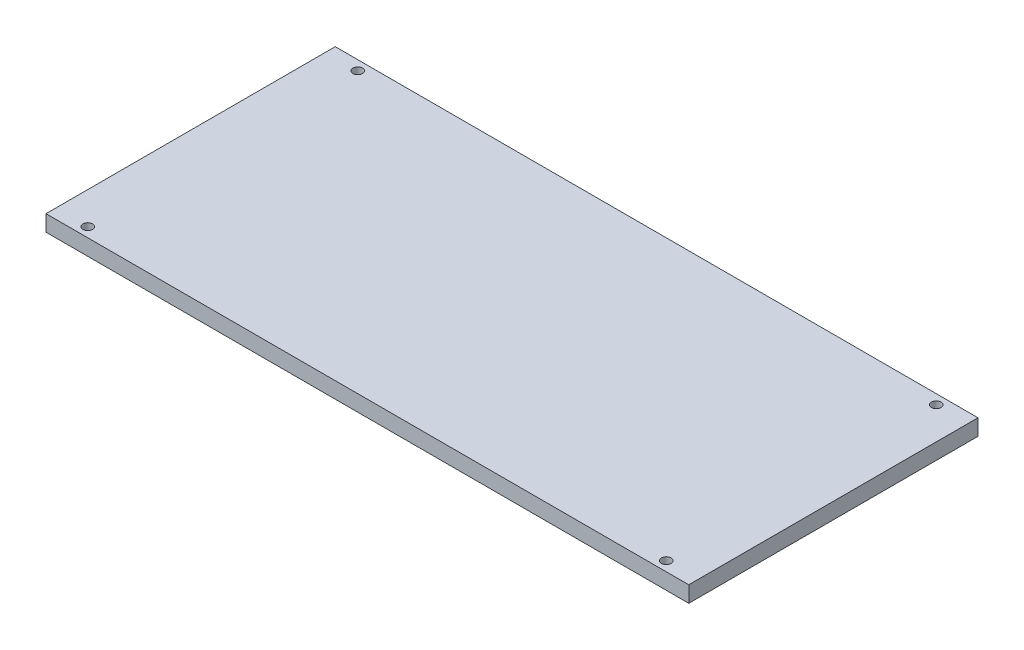
SolidWorks part; units mm, degrees
ref_plane "Front Plane" through (0, 0, 0) normal (0, 0, 1) x (1, 0, 0)
ref_plane "Top Plane" through (0, 0, 0) normal (0, 1, 0) x (1, 0, 0)
ref_plane "Right Plane" through (0, 0, 0) normal (1, 0, 0) x (0, 0, -1)
sketch "Sketch1" plane through (0, 0, 0) normal (0, 1, 0) x (1, 0, 0)
  line L1 (-96.0207, -6.3578) -> (103.9793, -6.3578)
  line L2 (-96.0207, -6.3578) -> (-96.0207, -96.3578)
  line L3 (-96.0207, -96.3578) -> (103.9793, -96.3578)
  line L4 (103.9793, -6.3578) -> (103.9793, -96.3578)
  circle A0 centre (-86.0207, -9.3578) radius 1.5
  circle A1 centre (-86.0207, -93.3578) radius 1.5
  circle A2 centre (93.9793, -9.3578) radius 1.5
  circle A3 centre (93.9793, -93.3578) radius 1.5
  point P12 (0, 0)
  point P13 (0, 0)
  point P14 (0, 0)
  point P15 (0, 0)
  point P16 (0, 0)
  dimension "D7" = 3
  dimension "D1" = 90
  dimension "D2" = 200
  dimension "D3" = 84
  dimension "D4" = 10
  dimension "D5" = 10
  dimension "D6" = 3
extrude "Boss-Extrude1" add sketch "Sketch1" along normal blind 5
